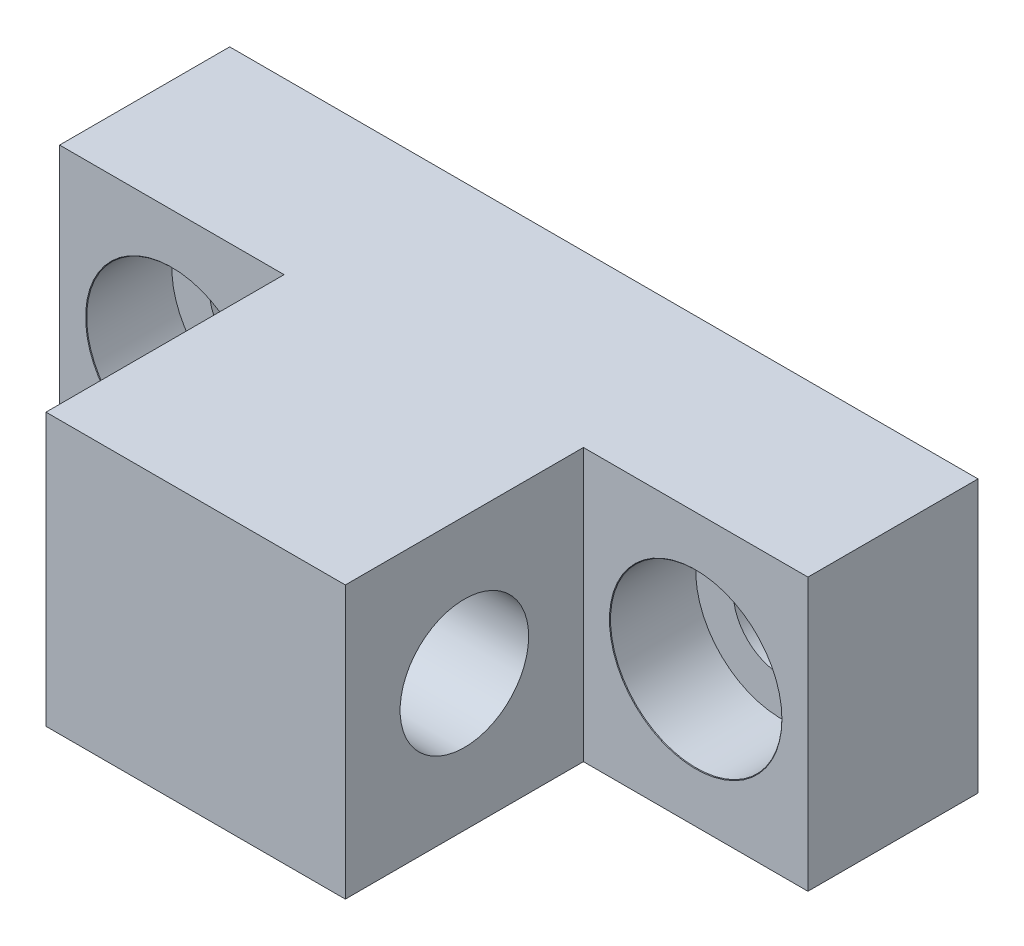
SolidWorks part; units mm, degrees
material "Custom Plastic"
ref_plane "X-Y Datum" through (0, 0, 0) normal (0, 0, 1) x (1, 0, 0)
ref_plane "X-Z Datum" through (0, 0, 0) normal (0, 1, 0) x (1, 0, 0)
ref_plane "Y-Z Datum" through (0, 0, 0) normal (1, 0, 0) x (0, 0, -1)
sketch "Sketch1" plane through (0, 0, 0) normal (0, 0, 1) x (1, 0, 0)
  line L0 (-17.4625, 0) -> (17.4625, 0) construction
  line L1 (-17.4625, 6.35) -> (17.4625, 6.35)
  line L2 (-17.4625, 6.35) -> (-17.4625, -6.35)
  line L3 (-17.4625, -6.35) -> (17.4625, -6.35)
  line L4 (17.4625, 6.35) -> (17.4625, -6.35)
  line L5 (-17.4625, 6.35) -> (17.4625, -6.35) construction
  line L6 (-17.4625, -6.35) -> (17.4625, 6.35) construction
  line L7 (0, 8.868) -> (0, -8.868) construction
  line L8 (-6.985, 6.35) -> (6.985, 6.35)
  line L9 (-6.985, 6.35) -> (-6.985, -6.35)
  line L10 (-6.985, -6.35) -> (6.985, -6.35)
  line L11 (6.985, 6.35) -> (6.985, -6.35)
  line L12 (-6.985, 6.35) -> (6.985, -6.35) construction
  line L13 (-6.985, -6.35) -> (6.985, 6.35) construction
  line L14 (-17.4625, 0) -> (-6.985, 0) construction
  line L15 (-6.985, 0) -> (-12.2238, 0) construction
  circle A0 centre (-12.2238, 0) radius 3.5 construction
  circle A1 centre (12.2237, 0) radius 3.5 construction
  circle A2 centre (-12.2238, 0) radius 2
  circle A3 centre (12.2237, 0) radius 2
  point P0 (0, 0)
  point P8 (0, 0)
  point P18 (0, 0)
  dimension "D4" = 7
  dimension "D5" = 4
  dimension "D1" = 12.7
  dimension "D2" = 34.925
  dimension "D3" = 13.97
extrude "Boss-Extrude1" add sketch "Sketch1" along normal blind 7.9375 contours L1 L11 L3 L4 A3 | L11 L1 L9 L3 | L9 L1 L2 L3 A2 | A3 | A2
sketch "Sketch2" plane through (0, 0, 7.9375) normal (0, 0, 1) x (1, 0, 0)
  line L4 (6.985, 6.35) -> (-6.985, 6.35)
  line L5 (6.985, -6.35) -> (6.985, 6.35)
  line L6 (-6.985, -6.35) -> (6.985, -6.35)
  line L7 (-6.985, 6.35) -> (-6.985, -6.35)
  line L8 (6.985, 6.35) -> (-6.985, 6.35)
  line L9 (6.985, -6.35) -> (6.985, 6.35)
  line L10 (-6.985, -6.35) -> (6.985, -6.35)
  line L11 (-6.985, 6.35) -> (-6.985, -6.35)
  line L12 (17.4625, 6.35) -> (-17.4625, 6.35)
  line L13 (17.4625, -6.35) -> (17.4625, 6.35)
  line L14 (-17.4625, -6.35) -> (17.4625, -6.35)
  line L15 (-17.4625, 6.35) -> (-17.4625, -6.35)
  line L16 (17.4625, 6.35) -> (-17.4625, 6.35)
  line L17 (17.4625, -6.35) -> (17.4625, 6.35)
  line L18 (-17.4625, -6.35) -> (17.4625, -6.35)
  line L19 (-17.4625, 6.35) -> (-17.4625, -6.35)
  circle A1 centre (12.2237, 0) radius 2
  circle A2 centre (12.2237, 0) radius 2
  circle A3 centre (-12.2238, 0) radius 2
  circle A4 centre (-12.2238, 0) radius 2
  line M11 (17.4625, 6.35) -> (-17.4625, 6.35)
  line M13 (-17.4625, -6.35) -> (17.4625, -6.35)
  dimension "D1" = 0
  dimension "D2" = 0
  dimension "D3" = 0
  dimension "D4" = 0
extrude "Boss-Extrude2" add sketch "Sketch2" along normal blind 11.1125 contours L11 L9 M11 M13
sketch "Sketch3" plane through (6.985, 0, 0) normal (1, 0, 0) x (0, 0, -1)
  line L0 (-13.4937, -6.35) -> (-13.4937, 6.35) construction
  line L4 (-7.9375, -6.35) -> (-7.9375, 6.35)
  line L5 (-7.9375, 6.35) -> (-19.05, 6.35)
  line L6 (-19.05, 6.35) -> (-19.05, -6.35)
  line L7 (-19.05, -6.35) -> (-7.9375, -6.35)
  line L8 (-7.9375, -6.35) -> (-7.9375, 6.35)
  line L9 (-7.9375, 6.35) -> (-19.05, 6.35)
  line L10 (-19.05, 6.35) -> (-19.05, -6.35)
  line L11 (-19.05, -6.35) -> (-7.9375, -6.35)
  circle A0 centre (-13.4937, 0) radius 3
  circle A1 centre (-13.4937, 0) radius 1.143
  dimension "D2" = 6
  dimension "D3" = 2.286
  dimension "D1" = 0
extrude "Cut-Extrude1" cut sketch "Sketch3" against normal blind 11.43 contours L0 A0 A1 | A0 L0 A1 | L0 A1 | A1 L0
sketch "Sketch4" plane through (6.985, 0, 0) normal (1, 0, 0) x (0, 0, -1)
  line L4 (-7.9375, -6.35) -> (-7.9375, 6.35)
  line L5 (-7.9375, 6.35) -> (-19.05, 6.35)
  line L6 (-19.05, 6.35) -> (-19.05, -6.35)
  line L7 (-19.05, -6.35) -> (-7.9375, -6.35)
  line L8 (-7.9375, -6.35) -> (-7.9375, 6.35)
  line L9 (-7.9375, 6.35) -> (-19.05, 6.35)
  line L10 (-19.05, 6.35) -> (-19.05, -6.35)
  line L11 (-19.05, -6.35) -> (-7.9375, -6.35)
  circle A1 centre (-13.4937, 0) radius 1.143
  circle A2 centre (-13.4937, 0) radius 1.143
  circle A3 centre (-13.4937, 0) radius 3
  circle A4 centre (-13.4937, 0) radius 3
  dimension "D1" = 0
  dimension "D2" = 0
  dimension "D3" = 0
extrude "Cut-Extrude2" cut sketch "Sketch4" against normal through all contours A2
hole_wizard "CBORE for M4 SHCS1" positions "Sketch7" profile "Sketch6" counterbore size "M4" standard "ANSI Metric" end condition through all
sketch "Sketch7" plane through (0, 0, 7.9375) normal (0, 0, 1) x (1, 0, 0)
  point P0 (12.2237, 0)
  point P3 (-12.2238, 0)
sketch "Sketch6" plane through (12.2237, 0, 7.9375) normal (1, 0, 0) x (0, -1, 0)
  line L0 (0, 0) -> (0, 7.9375)
  line L1 (0, 7.9375) -> (2.25, 7.9375)
  line L3 (2.25, 7.9375) -> (2.25, 4)
  line L4 (4, 4) -> (2.25, 4)
  line L5 (4, 4) -> (4, 0.025)
  line L6 (4, 0.025) -> (4.025, 0)
  line L7 (4.025, 0) -> (0, 0)
  line L8 (-4, 0.025) -> (-4.025, 0) construction
  line L11 (0, -6.35) -> (0, 107.95) construction
  dimension "Thru Hole Dia." = 4.5
  dimension "Thru Hole Depth" = 7.9375
  dimension "C'Bore Dia." = 8
  dimension "C'Bore Depth" = 4
  dimension "Near C'Sink Dia." = 8.05
  dimension "Near C'Sink Angle" = 90
sketch "Sketch8" plane through (6.985, 0, 0) normal (1, 0, 0) x (0, 0, -1)
  line L4 (-7.9375, -6.35) -> (-7.9375, 6.35)
  line L5 (-7.9375, 6.35) -> (-19.05, 6.35)
  line L6 (-19.05, 6.35) -> (-19.05, -6.35)
  line L7 (-19.05, -6.35) -> (-7.9375, -6.35)
  line L8 (-7.9375, -6.35) -> (-7.9375, 6.35)
  line L9 (-7.9375, 6.35) -> (-19.05, 6.35)
  line L10 (-19.05, 6.35) -> (-19.05, -6.35)
  line L11 (-19.05, -6.35) -> (-7.9375, -6.35)
  circle A1 centre (-13.4937, 0) radius 1.143
  circle A2 centre (-13.4937, 0) radius 1.143
  circle A3 centre (-13.4937, 0) radius 3
  circle A4 centre (-13.4937, 0) radius 3
  circle M7 centre (-13.4937, 0) radius 3
  dimension "D1" = 0
  dimension "D2" = 0
  dimension "D3" = 0
extrude "Cut-Extrude3" cut sketch "Sketch8" against normal through all contours A2 M7 | A2
